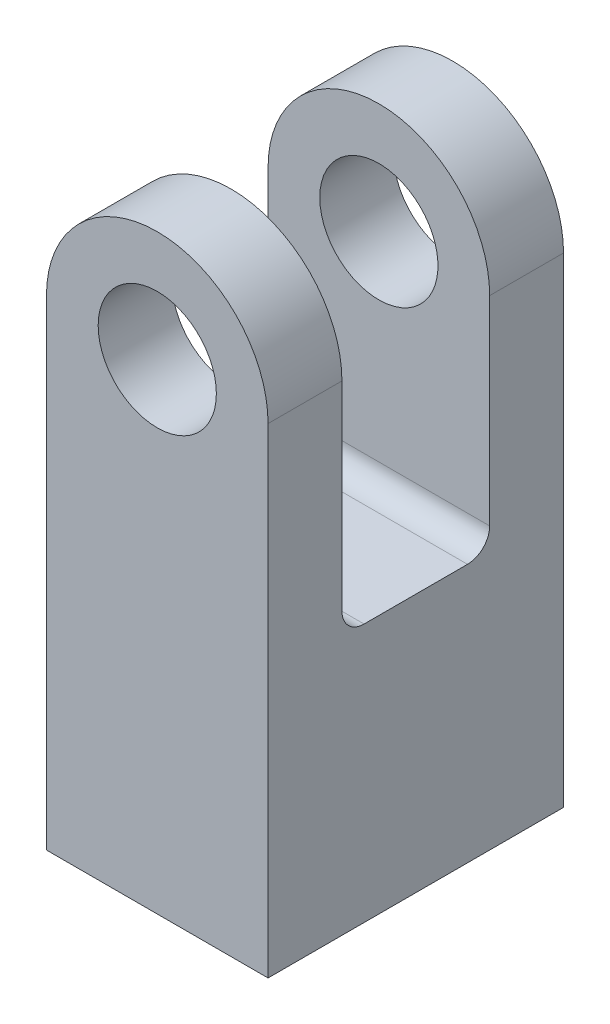
SolidWorks part; units mm, degrees
material "Простая углеродистая сталь"
ref_plane "Front" through (0, 0, 0) normal (0, 0, 1) x (1, 0, 0)
ref_plane "Top" through (0, 0, 0) normal (0, 1, 0) x (1, 0, 0)
ref_plane "Right" through (0, 0, 0) normal (1, 0, 0) x (0, 0, -1)
sketch "Эскиз1" plane through (0, 0, 0) normal (0, 0, 1) x (1, 0, 0)
  line L0 (0, 0) -> (30, 0)
  line L1 (30, 0) -> (30, 65)
  line L2 (0, 65) -> (0, 0)
  arc A0 (30, 65) -> (0, 65) centre (15, 65) ccw
  circle A1 centre (15, 65) radius 8
  point P7 (-15.4581, -4.3145)
  point P10 (0, 0)
  point P11 (0, 0)
  dimension "D1" = 16
  dimension "D2" = 30
  dimension "D3" = 65
extrude "Бобышка-Вытянуть1" add sketch "Эскиз1" along normal blind 40
sketch "Эскиз2" plane through (0, 0, 0) normal (0, 0, 1) x (1, 0, 0)
  line L0 (30, 0) -> (30, 65) construction
  line L1 (0, 35) -> (30, 35)
  line L2 (0, 35) -> (0, 80)
  line L3 (0, 80) -> (30, 80)
  line L4 (30, 35) -> (30, 80)
  line L5 (0, 65) -> (0, 0) construction
  arc A0 (30, 65) -> (0, 65) centre (15, 65) ccw construction
  circle A1 centre (15, 65) radius 8 construction
  dimension "D1" = 30
extrude "Вырез-Вытянуть1" cut sketch "Эскиз2" against normal mid plane 20 from offset 20
fillet "Скругление1" radius 3 2 edges at (15, 35, 30) (15, 35, 10)
